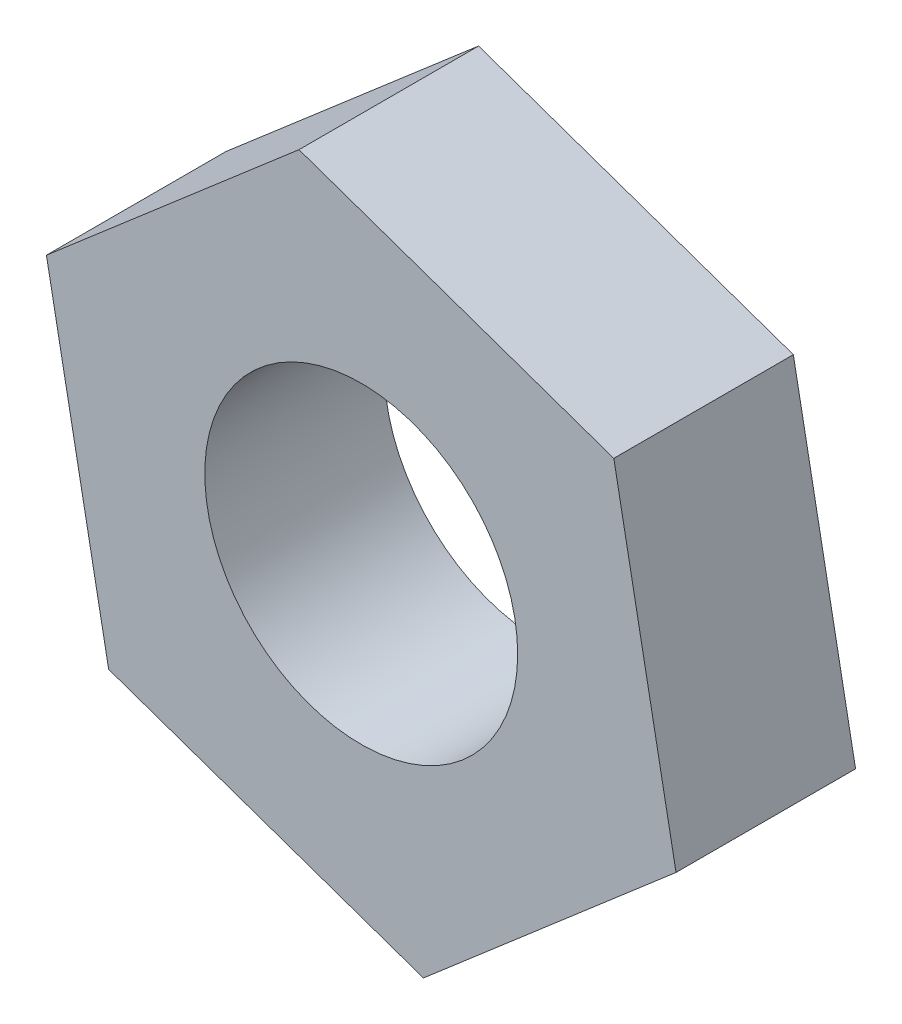
SolidWorks part; units mm, degrees
ref_plane "Front Plane" through (0, 0, 0) normal (0, 0, 1) x (1, 0, 0)
ref_plane "Top Plane" through (0, 0, 0) normal (0, 1, 0) x (1, 0, 0)
ref_plane "Right Plane" through (0, 0, 0) normal (1, 0, 0) x (0, 0, -1)
sketch "Sketch1" plane through (0, 0, 0) normal (0, 0, 1) x (1, 0, 0)
  line L1 (2.4256, -12.7717) -> (12.2734, -4.2852)
  line L2 (12.2734, -4.2852) -> (9.8478, 8.4865)
  line L3 (9.8478, 8.4865) -> (-2.4256, 12.7717)
  line L4 (-2.4256, 12.7717) -> (-12.2734, 4.2852)
  line L5 (-12.2734, 4.2852) -> (-9.8478, -8.4865)
  line L6 (-9.8478, -8.4865) -> (2.4256, -12.7717)
  circle A0 centre (0, 0) radius 11.2583 construction
  circle A1 centre (0, 0) radius 6.1
  dimension "D2" = 12.2
  dimension "D1" = 13
extrude "Boss-Extrude1" add sketch "Sketch1" along normal blind 7
